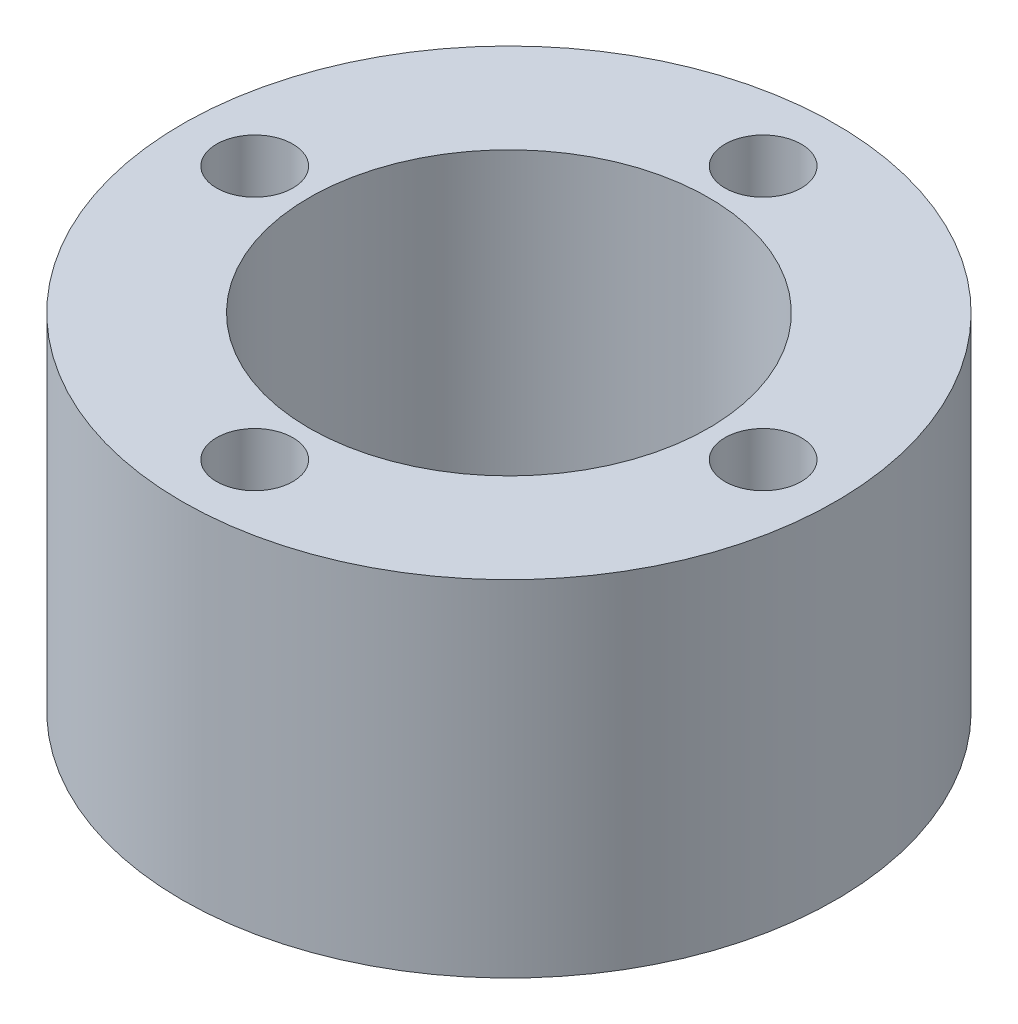
SolidWorks part; units mm, degrees
material "Esun Hard Tough Resin"
ref_plane "Front Plane" through (0, 0, 0) normal (0, 0, 1) x (1, 0, 0)
ref_plane "Top Plane" through (0, 0, 0) normal (0, 1, 0) x (1, 0, 0)
ref_plane "Right Plane" through (0, 0, 0) normal (1, 0, 0) x (0, 0, -1)
sketch "Sketch1" plane through (0, 0, 0) normal (0, 1, 0) x (1, 0, 0)
  circle A0 centre (0, 0) radius 9
  circle A1 centre (0, 7) radius 1.05
  circle A2 centre (7, 0) radius 1.05
  circle A3 centre (0, -7) radius 1.05
  circle A4 centre (-7, 0) radius 1.05
  circle A5 centre (0, 0) radius 5.5
  point P14 (0, 0)
  dimension "D1" = 18
  dimension "D2" = 2.1
  dimension "D5" = 11
  dimension "D3" = 7
  dimension "D4" = 4
extrude "Boss-Extrude1" add sketch "Sketch1" along normal blind 9.5
